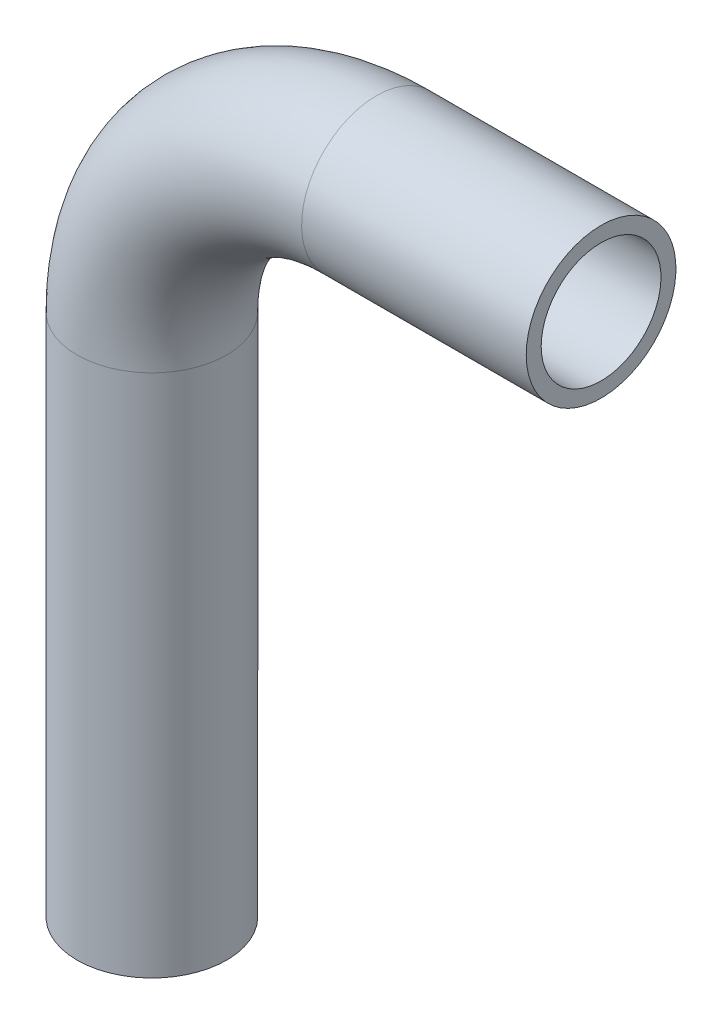
SolidWorks part; units mm, degrees
ref_plane "Front Plane" through (0, 0, 0) normal (0, 0, 1) x (1, 0, 0)
ref_plane "Top Plane" through (0, 0, 0) normal (0, 1, 0) x (1, 0, 0)
ref_plane "Right Plane" through (0, 0, 0) normal (1, 0, 0) x (0, 0, -1)
sketch "Sketch1" plane through (0, 0, 0) normal (0, 1, 0) x (1, 0, 0)
  circle A0 centre (0, 0) radius 12.7
  circle A1 centre (0, 0) radius 10.16
  dimension "D1" = 25.4
  dimension "D2" = 20.32
sketch "Sketch2" plane through (0, 0, 0) normal (0, 0, 1) x (1, 0, 0)
  line L0 (0, 0) -> (0, 88.9)
  line L1 (38.1, 127) -> (76.2, 127)
  arc A0 (0, 88.9) -> (38.1, 127) centre (38.1, 88.9) cw
  dimension "D1" = 88.9
  dimension "D2" = 38.1
  dimension "D3" = 38.1
sweep "Sweep1" add profiles "Sketch1" path "Sketch2"
